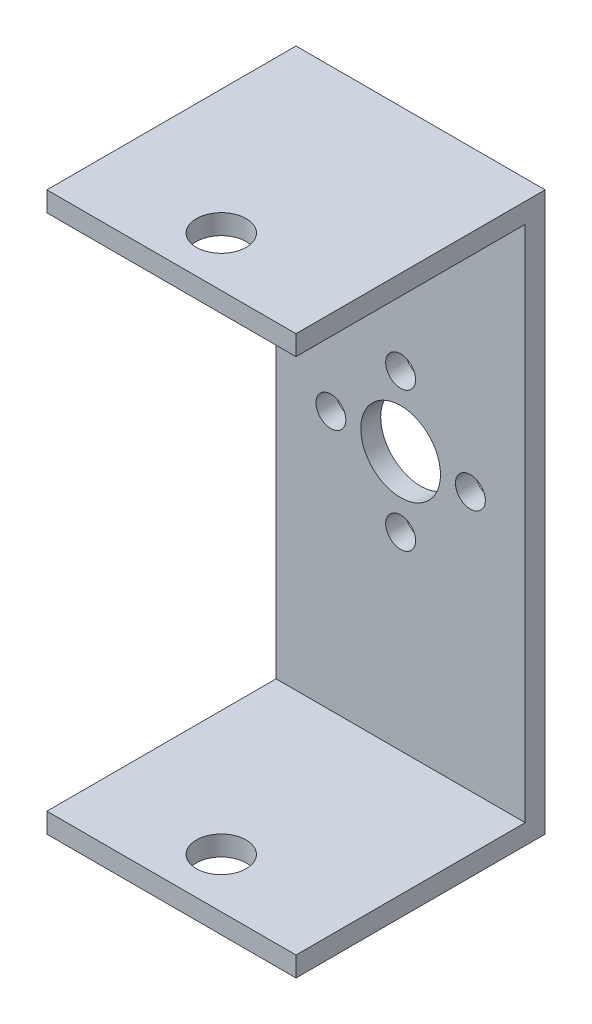
SolidWorks part; units mm, degrees
material "Plain Carbon Steel"
ref_plane "Front Plane" through (0, 0, 0) normal (0, 0, 1) x (1, 0, 0)
ref_plane "Top Plane" through (0, 0, 0) normal (0, 1, 0) x (1, 0, 0)
ref_plane "Right Plane" through (0, 0, 0) normal (1, 0, 0) x (0, 0, -1)
sketch "Sketch1" plane through (0, 0, 0) normal (0, 0, 1) x (1, 0, 0)
  line L1 (-12.6748, 30.5029) -> (12.3252, 30.5029)
  line L2 (-12.6748, 30.5029) -> (-12.6748, -21.4971)
  line L3 (-12.6748, -21.4971) -> (12.3252, -21.4971)
  line L4 (12.3252, 30.5029) -> (12.3252, -21.4971)
  dimension "D1" = 25
  dimension "D2" = 52
extrude "Boss-Extrude1" add sketch "Sketch1" along normal blind 2
sketch "Sketch2" plane through (0, 30.5029, 0) normal (0, 1, 0) x (1, 0, 0)
  line L1 (-12.6748, 0) -> (12.3252, 0)
  line L2 (-12.6748, 0) -> (-12.6748, -25)
  line L3 (-12.6748, -25) -> (12.3252, -25)
  line L4 (12.3252, 0) -> (12.3252, -25)
  dimension "D1" = 25
  dimension "D2" = 25
extrude "Boss-Extrude2" add sketch "Sketch2" along normal blind 2
sketch "Sketch3" plane through (0, -21.4971, 0) normal (0, -1, 0) x (-1, 0, 0)
  line L1 (-12.3252, 0) -> (12.6748, 0)
  line L2 (-12.3252, 0) -> (-12.3252, -25)
  line L3 (-12.3252, -25) -> (12.6748, -25)
  line L4 (12.6748, 0) -> (12.6748, -25)
  dimension "D1" = 25
  dimension "D2" = 25
extrude "Boss-Extrude3" add sketch "Sketch3" along normal blind 2
sketch "Sketch5" plane through (0, 0, 0) normal (0, 0, -1) x (-1, 0, 0)
  line L0 (12.6748, 32.5029) -> (12.6748, -23.4971) construction
  circle A0 centre (0.1748, 4.5029) radius 4
  dimension "D1" = 12.5
extrude "Cut-Extrude2" cut sketch "Sketch5" against normal blind 21
sketch "Sketch6" plane through (0, 0, 0) normal (0, 0, -1) x (-1, 0, 0)
  circle A0 centre (7.1748, 4.5029) radius 1.5
  circle A1 centre (0.1748, 4.5029) radius 4 construction
  circle A2 centre (0.1748, -2.4971) radius 1.5
  circle A3 centre (-6.8252, 4.5029) radius 1.5
  circle A4 centre (0.1748, 11.5029) radius 1.5
  point P13 (0.1748, 4.5029)
  dimension "D1" = 7
  dimension "D2" = 4
extrude "Cut-Extrude3" cut sketch "Sketch6" against normal blind 21
sketch "Sketch7" plane through (0, -23.4971, 0) normal (0, -1, 0) x (-1, 0, 0)
  line L0 (-12.3252, -25) -> (12.6748, -25) construction
  circle A0 centre (0.1748, -20) radius 2.5
  dimension "D1" = 5
extrude "Cut-Extrude4" cut sketch "Sketch7" against normal blind 81
